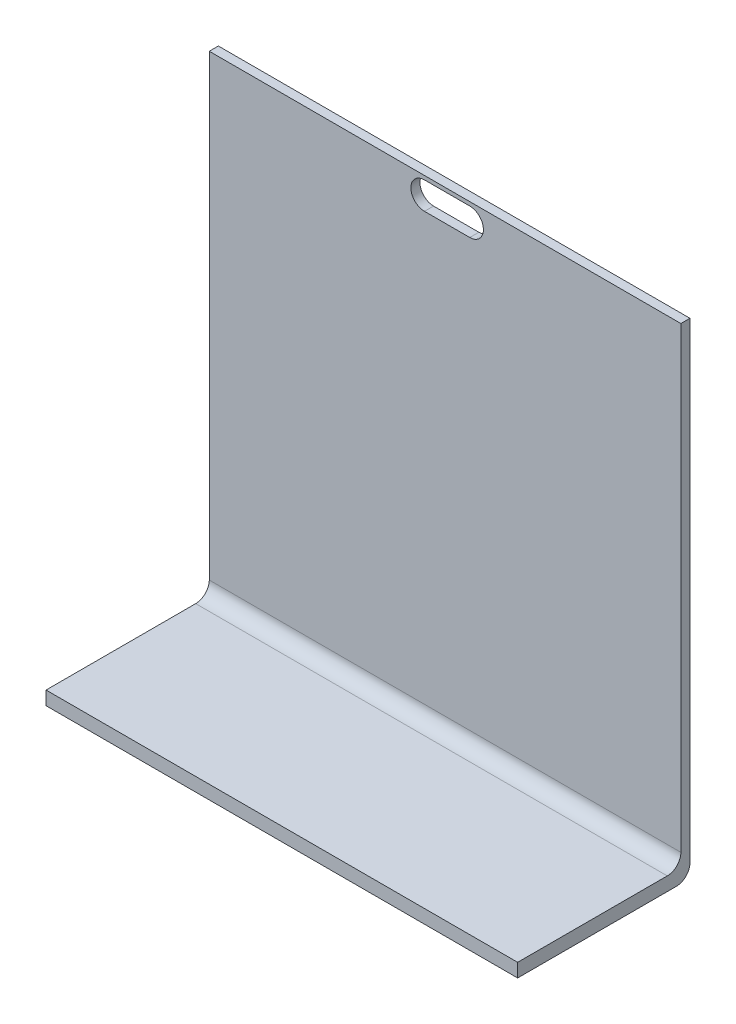
SolidWorks part; units mm, degrees
ref_plane "前视基准面" through (0, 0, 0) normal (0, 0, 1) x (1, 0, 0)
ref_plane "上视基准面" through (0, 0, 0) normal (0, 1, 0) x (1, 0, 0)
ref_plane "右视基准面" through (0, 0, 0) normal (1, 0, 0) x (0, 0, -1)
sketch "草图1" plane through (0, 0, 0) normal (0, 1, 0) x (1, 0, 0)
  line L1 (52, -19) -> (-52, -19)
  line L2 (52, -19) -> (52, 19)
  line L3 (52, 19) -> (-52, 19)
  line L4 (-52, -19) -> (-52, 19)
  line L5 (52, -19) -> (-52, 19) construction
  line L6 (52, 19) -> (-52, -19) construction
  point P0 (0, 0)
extrude "凸台-拉伸1" add sketch "草图1" along normal blind 3
sketch "草图2" plane through (0, 3, 0) normal (0, 1, 0) x (1, 0, 0)
  line L0 (-52, 19) -> (-52, -19) construction
  line L1 (52, 19) -> (-52, 19)
  line L2 (52, 19) -> (52, 17)
  line L3 (52, 17) -> (-52, 17)
  line L4 (-52, 19) -> (-52, 17)
extrude "凸台-拉伸3" add sketch "草图2" along normal blind 104
fillet "圆角1" radius 3 2 edges at (0, 0, -19) (0, 3, -17)
sketch "草图4" plane through (0, 0, -19) normal (0, 0, -1) x (-1, 0, 0)
  line L0 (52, 107) -> (52, 3) construction
  line L1 (-52, 107) -> (52, 107)
  line L2 (-52, 107) -> (-52, 104.6514)
  line L3 (-52, 104.6514) -> (52, 104.6514)
  line L4 (52, 107) -> (52, 104.6514)
  line L5 (-5.4521, 103.1546) -> (4.5438, 103.1546) construction
  line L6 (9.6933, 101.6578) -> (-10.6016, 101.6578)
  line L7 (9.6933, 101.6578) -> (9.6933, 104.6514)
  line L8 (9.6933, 104.6514) -> (-10.6016, 104.6514)
  line L9 (-10.6016, 101.6578) -> (-10.6016, 104.6514)
  line L10 (9.6933, 101.6578) -> (-10.6016, 104.6514) construction
  line L11 (9.6933, 104.6514) -> (-10.6016, 101.6578) construction
  line L12 (-5.4521, 106.1546) -> (4.5438, 106.1546)
  line L13 (-5.4521, 100.1546) -> (4.5438, 100.1546)
  arc A0 (-5.4521, 106.1546) -> (-5.4521, 100.1546) centre (-5.4521, 103.1546) ccw
  arc A1 (4.5438, 100.1546) -> (4.5438, 106.1546) centre (4.5438, 103.1546) ccw
  point P7 (-0.4542, 103.1546)
  point P14 (-0.4542, 103.1546)
extrude "切除-拉伸1" cut sketch "草图4" against normal through all contours A0 L13 A1 L12
